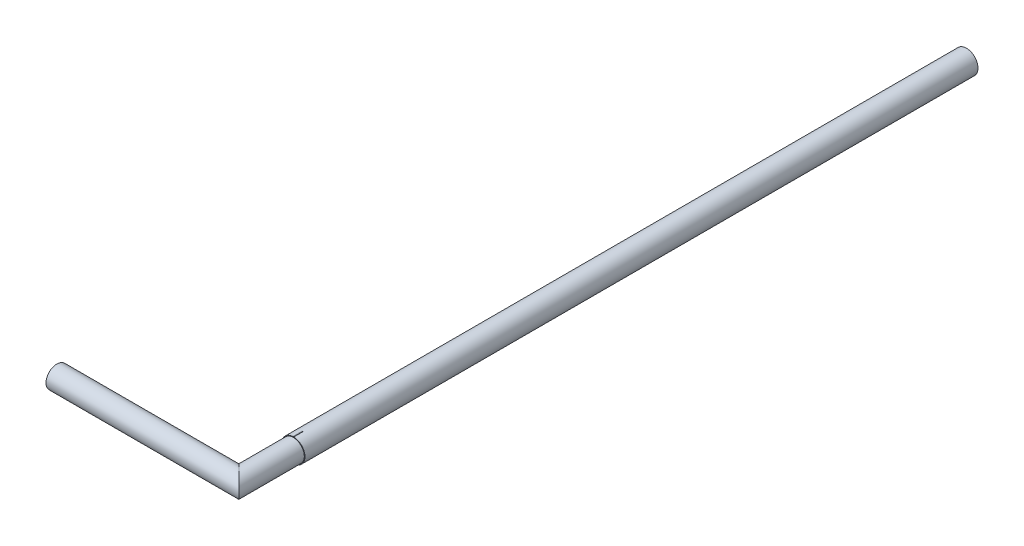
SolidWorks part; units mm, degrees
ref_plane "Alzado" through (0, 0, 0) normal (0, 0, 1) x (1, 0, 0)
ref_plane "Planta" through (0, 0, 0) normal (0, 1, 0) x (1, 0, 0)
ref_plane "Vista lateral" through (0, 0, 0) normal (1, 0, 0) x (0, 0, -1)
sketch "Croquis1" plane through (0, 0, 0) normal (0, 0, 1) x (1, 0, 0)
  circle A0 centre (0, 0) radius 12.7
  dimension "D1" = 25.4
extrude "Saliente-Extruir1" add sketch "Croquis1" along normal blind 740
sketch "Croquis2" plane through (0, 0, 740) normal (0, 0, 1) x (1, 0, 0)
  line L1 (-0.3886, 12.4119) -> (0.3886, 12.4119)
  line L2 (-0.3886, 12.4119) -> (-0.3886, 12.9881)
  line L3 (-0.3886, 12.9881) -> (0.3886, 12.9881)
  line L4 (0.3886, 12.4119) -> (0.3886, 12.9881)
  line L5 (-0.3886, 12.4119) -> (0.3886, 12.9881) construction
  line L6 (-0.3886, 12.9881) -> (0.3886, 12.4119) construction
  circle A0 centre (0, 0) radius 12.7 construction
  point P0 (0, 12.7)
extrude "Saliente-Extruir2" add sketch "Croquis2" against normal blind 10
sketch3d "Croquis3D1"
  line L0 (0, 0, 740) -> (0, 0, 800)
  line L1 (0, 0, 740) -> (0, 0, 730) construction
  line L2 (0, 0, 800) -> (-200, 0, 800)
  dimension "D1" = 60
  dimension "D2" = 200
sketch "Croquis3" plane through (0, 0, 740) normal (0, 0, 1) x (1, 0, 0)
  circle A0 centre (0, 0) radius 12
  dimension "D1" = 24
sweep "Barrer1" add profiles "Croquis3" path "Croquis3D1"
